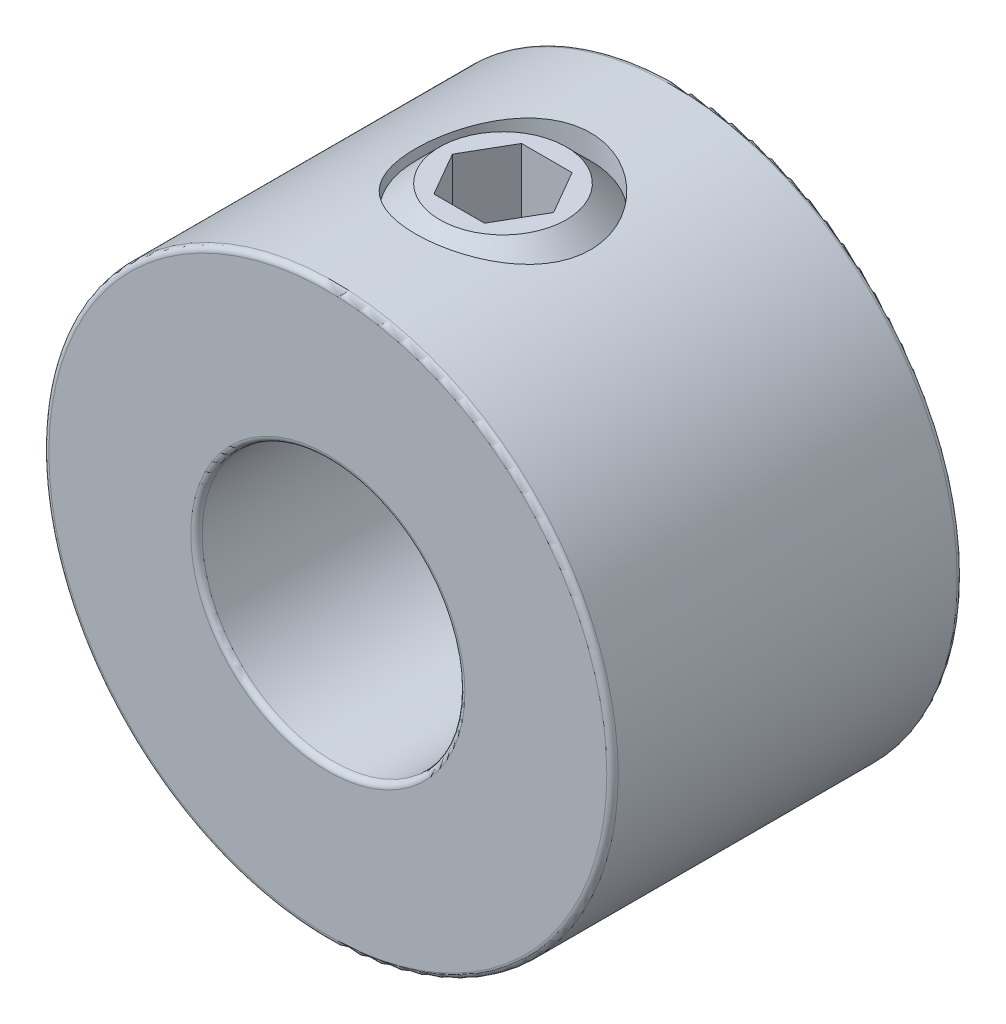
SolidWorks part; units mm, degrees
ref_plane "Front Plane" through (0, 0, 0) normal (0, 0, 1) x (1, 0, 0)
ref_plane "Top Plane" through (0, 0, 0) normal (0, 1, 0) x (1, 0, 0)
ref_plane "Right Plane" through (0, 0, 0) normal (1, 0, 0) x (0, 0, -1)
sketch "Sketch1" plane through (0, 0, 0) normal (0, 0, 1) x (1, 0, 0)
  circle A0 centre (0, 0) radius 6.5
  circle A1 centre (0, 0) radius 3
  point P4 (6.5, 0)
  point P5 (0, 6.5)
  dimension "Bore Dia" = 6
  dimension "OD" = 13
extrude "Extrude1" add sketch "Sketch1" along normal blind 8
ref_plane "Plane1" through (0, 6.5, 0) normal (0, 1, 0) x (-1, 0, 0)
sketch "Sketch2" plane through (0, 6.5, 0) normal (0, 1, 0) x (-1, 0, 0)
  line L0 (0, 0) -> (0, 8) construction
  line L2 (6.5, 8) -> (-6.5, 8) construction
  circle A0 centre (0, 4) radius 2
  dimension "Set Screw Dia" = 4
extrude "Cut-Extrude1" cut sketch "Sketch2" against normal up to surface (6.5 mm away) up to plane "Top Plane"
ref_plane "Plane2" through (0, 0, 4) normal (0, 0, 1) x (1, 0, 0)
sketch "Sketch3" plane through (0, 0, 4) normal (0, 0, 1) x (1, 0, 0)
  line L0 (-1.4434, 6.5) -> (-2, 5.9434)
  line L1 (0, 3.366) -> (0, 6.5)
  line L2 (-0.5, 2.5) -> (-1.4434, 2.5)
  line L3 (-2, 3.0566) -> (-2, 5.9434)
  line L4 (0, 6.5) -> (-1.4434, 6.5)
  line L5 (0, 2.5) -> (0, 0) construction
  line L6 (-2, 5.9434) -> (0, 5.9434) construction
  line L7 (0, 3.366) -> (-0.5, 2.5)
  line L8 (-1.4434, 2.5) -> (-2, 3.0566)
  point P1 (-0.5, 2.5)
  dimension "D1" = 2.8868
  dimension "Screw Length" = 4
  dimension "D2" = 45
  dimension "D3" = 4
  dimension "D4" = 45
  dimension "D5" = 60
  dimension "D7" = 2
  dimension "D8" = 0.5
revolve "Revolve1" add sketch "Sketch3" angle 360 about L1
sketch "Sketch4" plane through (0, 6.5, 0) normal (0, 1, 0) x (0, 0, -1)
  line L0 (-4, 1.1547) -> (-4, -1.1547) construction
  line L1 (-4, 1.1547) -> (-5, 0.5774)
  line L2 (-5, 0.5774) -> (-5, -0.5774)
  line L3 (-5, -0.5774) -> (-4, -1.1547)
  line L4 (-4, -1.1547) -> (-3, -0.5774)
  line L5 (-3, -0.5774) -> (-3, 0.5774)
  line L6 (-3, 0.5774) -> (-4, 1.1547)
  circle A0 centre (-4, 0) radius 1 construction
  circle A1 centre (-4, 0) radius 1.1547 construction
  dimension "D1" = 2.3094
  dimension "Hex" = 2
extrude "Cut-Extrude2" cut sketch "Sketch4" against normal blind 1.6
fillet "Fillet1" radius 0.13 4 edges at (3, 0, 0) (3, 0, 8) (6.5, 0, 0) (6.5, 0, 8)
equation "\"D3@Sketch3\" = \"Set Screw Dia@Sketch2\""
equation "\"D1@Fillet1\" = \"OD@Sketch1\"*.01"
equation "\"D1@Sketch3\" = \"D1@Sketch4\"*1.25"
equation "\"D1@Cut-Extrude2\" = \"Hex@Sketch4\"*.8"
equation "\"D8@Sketch3\" = \"D7@Sketch3\"/4"
